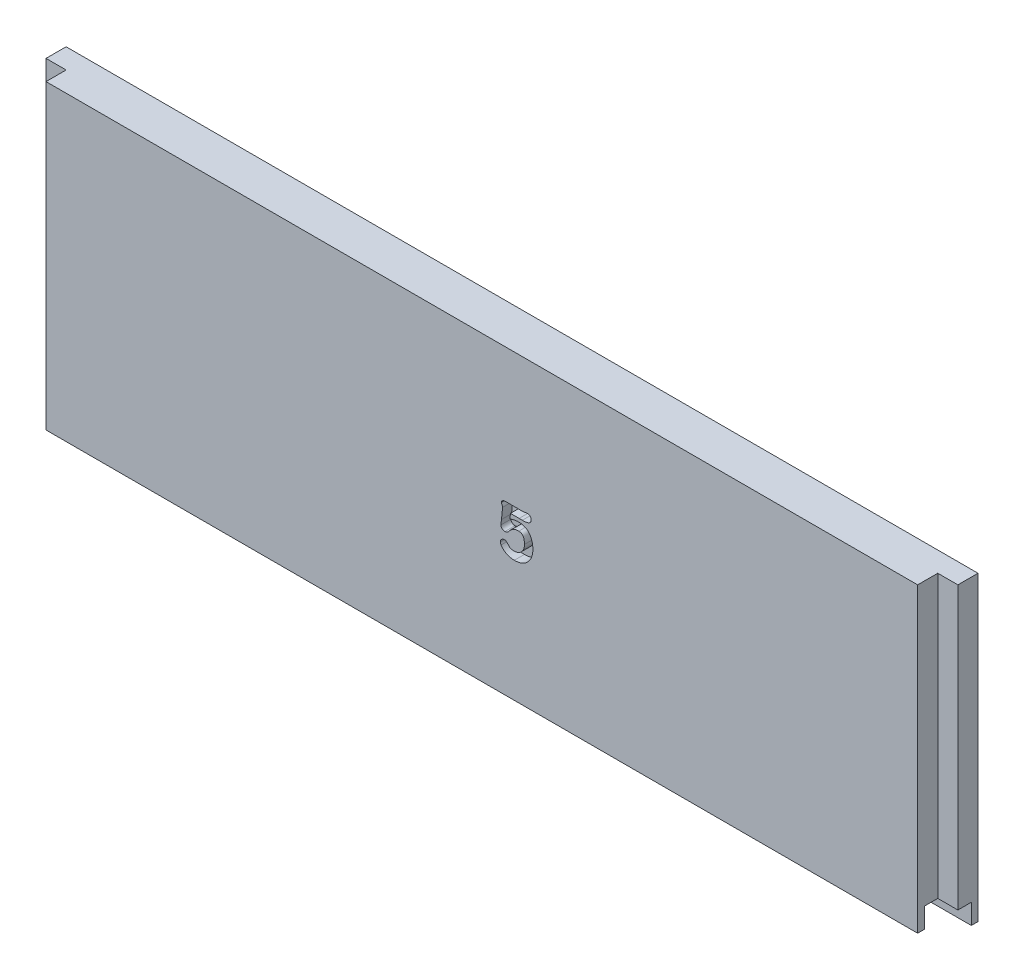
SolidWorks part; units mm, degrees
material "ABS"
ref_plane "前基準面" through (0, 0, 0) normal (0, 0, 1) x (1, 0, 0)
ref_plane "上基準面" through (0, 0, 0) normal (0, 1, 0) x (1, 0, 0)
ref_plane "右基準面" through (0, 0, 0) normal (1, 0, 0) x (0, 0, -1)
sketch "草圖1" plane through (0, 0, 0) normal (0, 0, 1) x (1, 0, 0)
  line L1 (-52.0363, -26.5774) -> (77.9637, -26.5774)
  line L2 (-52.0363, -26.5774) -> (-52.0363, -71.5774)
  line L3 (-52.0363, -71.5774) -> (77.9637, -71.5774)
  line L4 (77.9637, -26.5774) -> (77.9637, -71.5774)
  dimension "D1" = 130
  dimension "D2" = 45
extrude "填料-伸長1" add sketch "草圖1" along normal blind 6
sketch "草圖2" plane through (-52.0363, 0, 0) normal (-1, 0, 0) x (0, 0, 1)
  line L0 (6, -26.5774) -> (0, -26.5774) construction
  line L1 (3, -26.5774) -> (0, -26.5774)
  line L2 (3, -26.5774) -> (3, -71.5774)
  line L3 (3, -71.5774) -> (0, -71.5774)
  line L4 (0, -26.5774) -> (0, -71.5774)
extrude "填料-伸長2" add sketch "草圖2" along normal blind 3 and the other way blind 133
sketch "草圖3" plane through (0, -71.5774, 0) normal (0, -1, 0) x (1, 0, 0)
  line L1 (-55.0363, 1) -> (80.9637, 1)
  line L2 (-55.0363, 1) -> (-55.0363, 3)
  line L3 (-55.0363, 3) -> (80.9637, 3)
  line L4 (80.9637, 1) -> (80.9637, 3)
  line L6 (77.9637, 5) -> (-52.0363, 5)
  line L7 (77.9637, 5) -> (77.9637, 3)
  line L8 (77.9637, 3) -> (-52.0363, 3)
  line L9 (-52.0363, 5) -> (-52.0363, 3)
  line L10 (-55.0363, 0) -> (80.9637, 0) construction
  point P4 (0, 0)
  point P14 (0, 0)
  line M1 (-52.0363, 6) -> (-52.0363, 3)
  line M2 (-52.0363, 3) -> (-55.0363, 3)
  line M3 (-55.0363, 3) -> (-55.0363, 0)
  line M5 (80.9637, 0) -> (80.9637, 3)
  line M6 (80.9637, 3) -> (77.9637, 3)
  line M7 (77.9637, 3) -> (77.9637, 6)
  dimension "D1" = 1
  dimension "D2" = 4
extrude "除料-伸長1" cut sketch "草圖3" against normal blind 3 contours L6 L3 M7 M1 | L3 L1 M2 M3 M5 M6
sketch "草圖4" plane through (0, 0, 6) normal (0, 0, 1) x (1, 0, 0)
  text T0 "5" font "Comic Sans MS" height in points 24
extrude "除料-伸長2" cut sketch "草圖4" against normal blind 1.5
